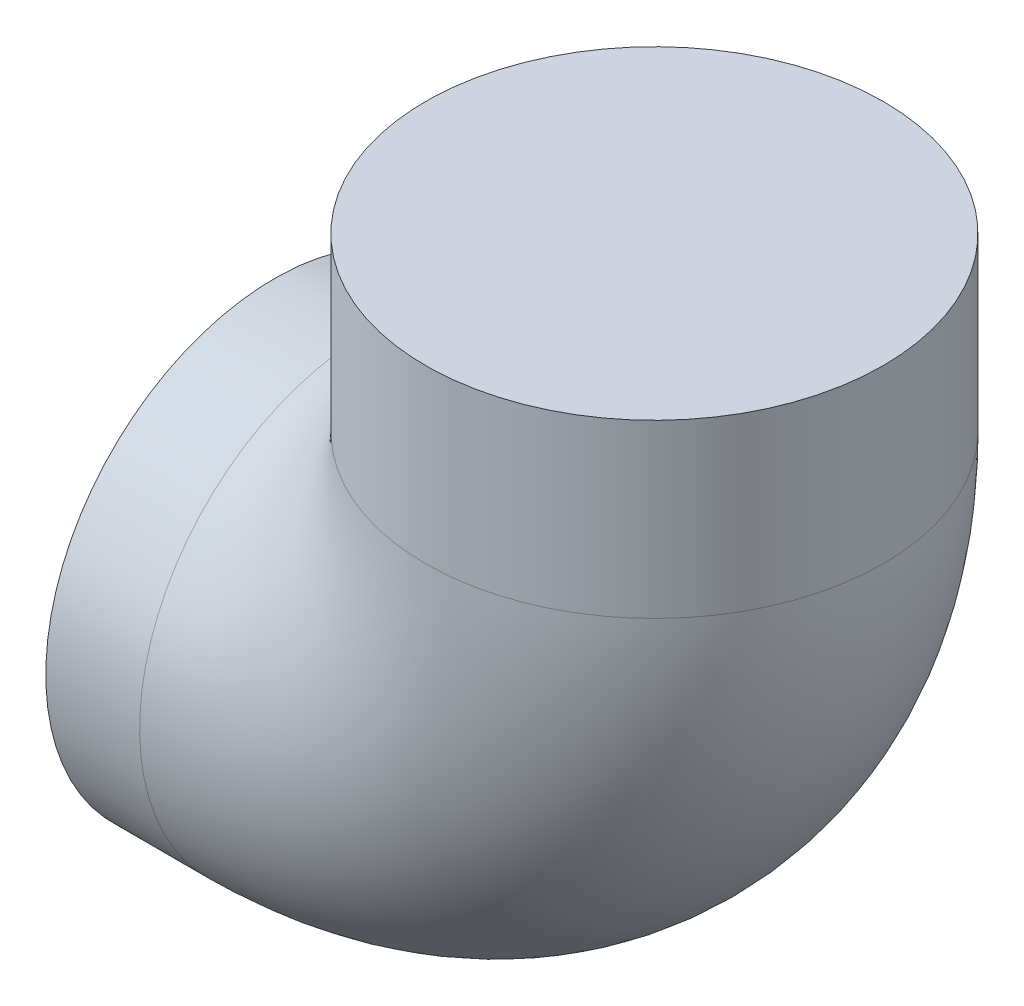
SolidWorks part; units mm, degrees
ref_plane "Front Plane" through (0, 0, 0) normal (0, 0, 1) x (1, 0, 0)
ref_plane "Top Plane" through (0, 0, 0) normal (0, 1, 0) x (1, 0, 0)
ref_plane "Right Plane" through (0, 0, 0) normal (1, 0, 0) x (0, 0, -1)
sketch "Sketch1" plane through (0, 0, 0) normal (0, 0, 1) x (1, 0, 0)
  line L0 (0, 0) -> (8.2, 0)
  line L1 (33.2, 25) -> (33.2, 40)
  arc A0 (8.2, 0) -> (33.2, 25) centre (8.2, 25) ccw
  point P6 (33.2, 0)
  dimension "D3" = 25
  dimension "D1" = 33.2
  dimension "D2" = 40
sketch "Sketch2" plane through (0, 0, 0) normal (1, 0, 0) x (0, 0, -1)
  circle A0 centre (0, 0) radius 20
  dimension "D1" = 40
sweep "Sweep2" add profiles "Sketch2" path "Sketch1"
